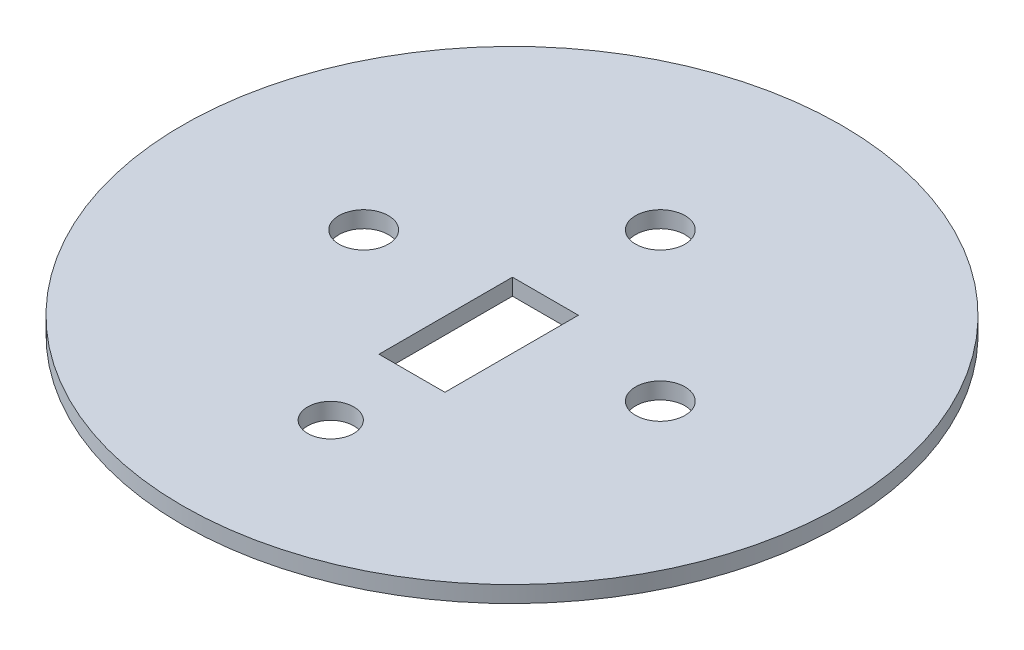
SolidWorks part; units mm, degrees
ref_plane "Alzado" through (0, 0, 0) normal (0, 0, 1) x (1, 0, 0)
ref_plane "Planta" through (0, 0, 0) normal (0, 1, 0) x (1, 0, 0)
ref_plane "Vista lateral" through (0, 0, 0) normal (1, 0, 0) x (0, 0, -1)
sketch "Sketch2" plane through (0, 0, 0) normal (0, 1, 0) x (1, 0, 0)
  circle A0 centre (0, 0) radius 100
extrude "Boss-Extrude1" add sketch "Sketch2" along normal mid plane 5
sketch "Sketch3" plane through (0, -2.5, 0) normal (0, -1, 0) x (1, 0, 0)
  line L0 (-55, 0) -> (0, 0) construction
  line L1 (0, 0) -> (0, -66.1396) construction
  line L2 (-65, 0) -> (-65, -50)
  line L3 (-65, -50) -> (-55, -50)
  line L4 (-55, -50) -> (-55, 50)
  line L5 (-55, 50) -> (-65, 50)
  line L6 (-65, 50) -> (-65, 0)
  line L7 (55, 50) -> (65, 50)
  line L8 (65, 50) -> (65, 0)
  line L9 (65, -50) -> (55, -50)
  line L10 (65, 0) -> (65, -50)
  line L11 (55, -50) -> (55, 50)
  dimension "D1" = 50
  dimension "D2" = 10
  dimension "D3" = 100
extrude "Cut-Extrude1" cut sketch "Sketch3" against normal blind 2.5
sketch "Sketch5" plane through (0, -2.5, 0) normal (0, -1, 0) x (1, 0, 0)
  line L0 (0, 0) -> (0, 30.36) construction
  line L1 (0, 30.36) -> (10, 30.36)
  line L2 (10, 30.36) -> (10, -10.14)
  line L3 (10, -10.14) -> (-10, -10.14)
  line L4 (-10, -10.14) -> (-10, 30.36)
  line L5 (-10, 30.36) -> (0, 30.36)
  dimension "D1" = 30.36
  dimension "D2" = 10
  dimension "D3" = 40.5
  dimension "D4" = 20
extrude "Cut-Extrude2" cut sketch "Sketch5" against normal blind 10
sketch "Sketch6" plane through (0, -2.5, 0) normal (0, -1, 0) x (1, 0, 0)
  line L0 (0, 0) -> (0, -45) construction
  line L1 (0, 0) -> (0, 55) construction
  line L2 (0, 0) -> (45, 0) construction
  line L3 (0, 0) -> (-45, 0) construction
  circle A0 centre (-45, 0) radius 7.5
  circle A1 centre (0, -45) radius 7.5
  circle A2 centre (45, 0) radius 7.5
  circle A3 centre (0, 55) radius 7
  dimension "D3" = 45
  dimension "D1" = 55
  dimension "D2" = 45
extrude "Cut-Extrude3" cut sketch "Sketch6" against normal blind 10
